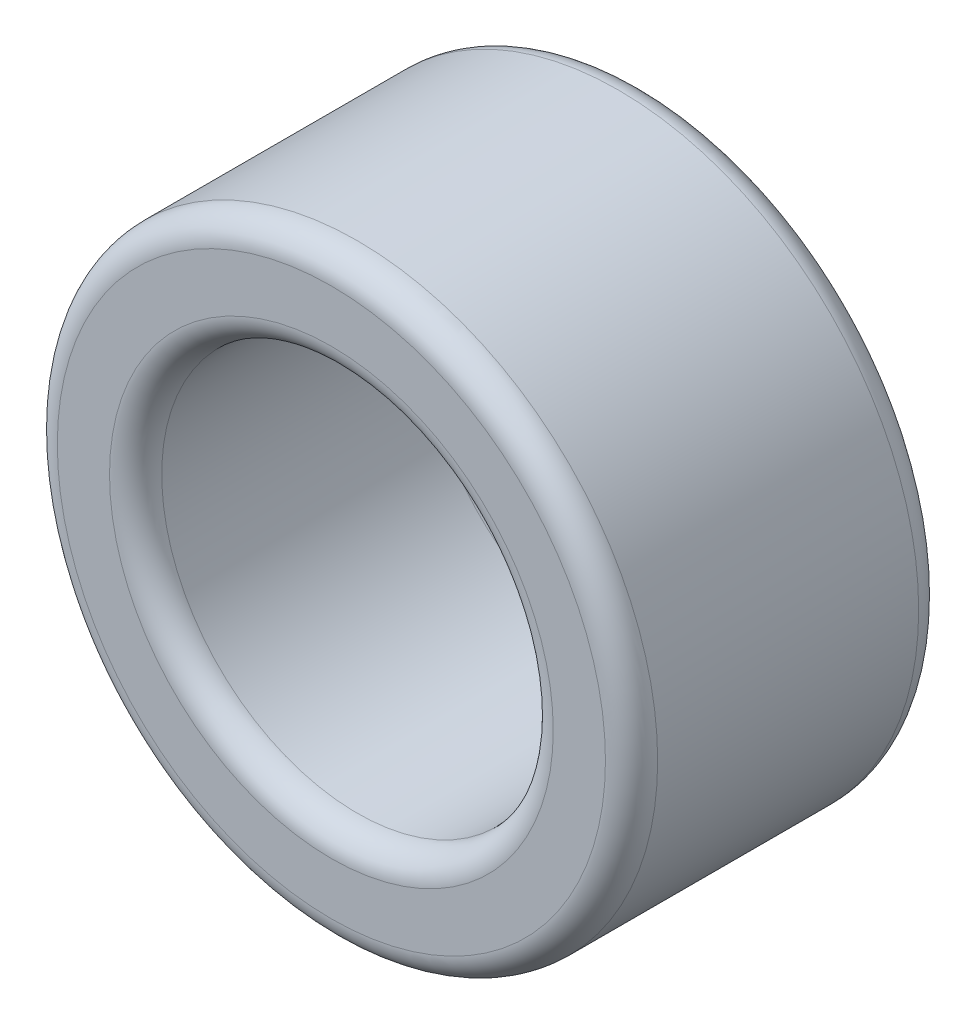
SolidWorks part; units mm, degrees
material "ABS PC"
ref_plane "Front Plane" through (0, 0, 0) normal (0, 0, 1) x (1, 0, 0)
ref_plane "Top Plane" through (0, 0, 0) normal (0, 1, 0) x (1, 0, 0)
ref_plane "Right Plane" through (0, 0, 0) normal (1, 0, 0) x (0, 0, -1)
sketch "Sketch1" plane through (0, 0, 0) normal (0, 0, 1) x (1, 0, 0)
  circle A0 centre (0, 0) radius 0.75
  circle A1 centre (0, 0) radius 1.15
  dimension "D1" = 1.5
  dimension "D2" = 2.3
extrude "Boss-Extrude1" add sketch "Sketch1" along normal blind 1.2
fillet "Fillet1" radius 0.1 4 edges at (0.75, 0, 0) (1.15, 0, 0) (1.15, 0, 1.2) (0.75, 0, 1.2)
